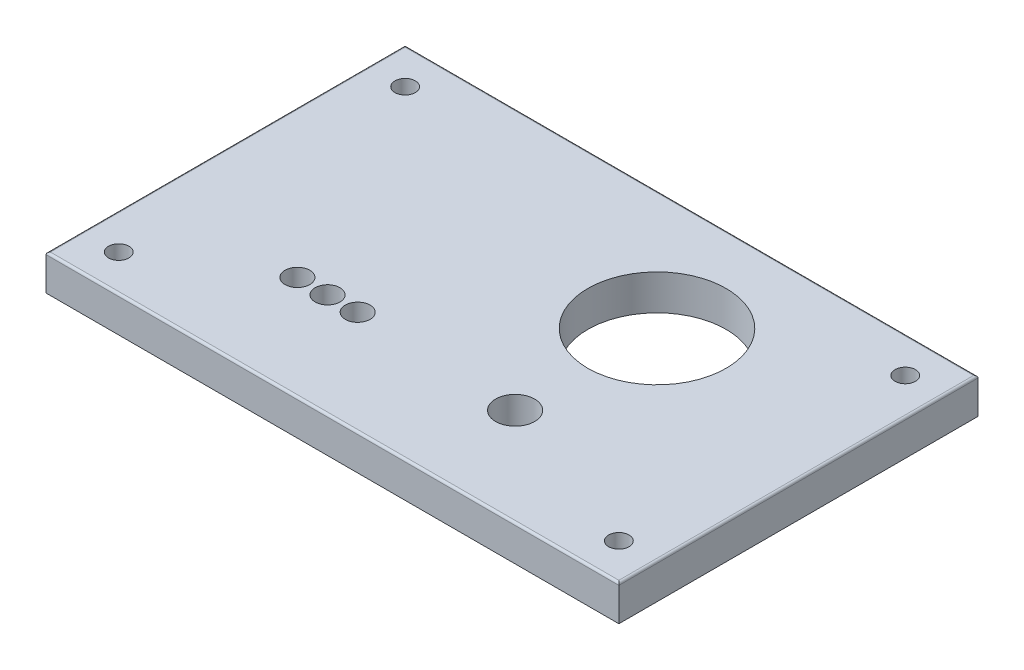
SolidWorks part; units mm, degrees
ref_plane "Front Plane" through (0, 0, 0) normal (0, 0, 1) x (1, 0, 0)
ref_plane "Top Plane" through (0, 0, 0) normal (0, 1, 0) x (1, 0, 0)
ref_plane "Right Plane" through (0, 0, 0) normal (1, 0, 0) x (0, 0, -1)
sketch "Sketch1" plane through (0, 0, 0) normal (0, 1, 0) x (1, 0, 0)
  line L0 (32.3, 20.25) -> (32.3, 17.75) construction
  line L1 (-32.3, -20.25) -> (32.3, -20.25)
  line L2 (-32.3, -20.25) -> (-32.3, 20.25)
  line L3 (-32.3, 20.25) -> (32.3, 20.25)
  line L4 (32.3, -20.25) -> (32.3, 20.25)
  line L5 (-32.3, -20.25) -> (32.3, 20.25) construction
  line L6 (-32.3, 20.25) -> (32.3, -20.25) construction
  line L7 (32.3, 17.75) -> (29.8, 17.75) construction
  line L8 (29.8, 17.75) -> (29.8, 20.25) construction
  line L9 (-2.2, 6.75) -> (1.8, 6.75) construction
  line L10 (29.8, 17.75) -> (-2.2, 17.75) construction
  line L11 (29.8, 17.75) -> (29.8, -4.25) construction
  line L12 (29.8, -4.25) -> (-2.2, -4.25) construction
  line L13 (-2.2, 17.75) -> (-2.2, -4.25)
  line L14 (1.8, 6.75) -> (9.6, 6.75) construction
  line L15 (9.6, 6.75) -> (9.6, -4.25) construction
  line L16 (9.6, -4.25) -> (9.6, -6.75) construction
  line L17 (9.6, -6.75) -> (9.6, -11.75) construction
  line L18 (-2.2, 6.75) -> (-4.7, 6.75) construction
  line L19 (-4.7, 6.75) -> (-19.8, 6.75) construction
  line L20 (-12.25, 6.75) -> (-12.25, 18.55) construction
  line L21 (-12.25, 18.55) -> (-4.7, 18.55)
  line L22 (-12.25, 18.55) -> (-19.8, 18.55) construction
  line L23 (-19.8, -8.55) -> (-4.7, -8.55) construction
  line L24 (-19.8, 18.55) -> (-4.7, 18.55) construction
  line L25 (-19.8, 18.55) -> (-19.8, -6.55) construction
  line L26 (-19.8, -6.55) -> (-4.7, -6.55) construction
  line L27 (-4.7, 18.55) -> (-4.7, -6.55) construction
  line L28 (-10.85, -8.55) -> (-10.25, -8.55) construction
  line L29 (-10.25, -8.55) -> (-8.85, -8.55) construction
  line L30 (-13.65, -8.55) -> (-14.25, -8.55) construction
  line L31 (-14.25, -8.55) -> (-15.65, -8.55) construction
  circle A0 centre (9.6, 6.75) radius 7.8
  circle A1 centre (9.6, -9.25) radius 2.2
  circle A2 centre (-12.25, -8.55) radius 1.4
  circle A3 centre (-8.85, -8.55) radius 1.4
  circle A4 centre (-15.65, -8.55) radius 1.4
  point P0 (0, 0)
  dimension "D9" = 15.6
  dimension "D11" = 5
  dimension "D12" = 4.4
  dimension "D20" = 2.8
  dimension "D23" = 2.8
  dimension "D26" = 2.8
  dimension "D1" = 40.5
  dimension "D2" = 64.6
  dimension "D3" = 2.5
  dimension "D4" = 2.5
  dimension "D5" = 32
  dimension "D6" = 22
  dimension "D7" = 4
  dimension "D8" = 7.8
  dimension "D10" = 2.5
  dimension "D13" = 2.5
  dimension "D14" = 15.1
  dimension "D15" = 7.55
  dimension "D16" = 7.55
  dimension "D17" = 25.1
  dimension "D18" = 15.1
  dimension "D21" = 0.6
  dimension "D22" = 1.4
  dimension "D24" = 0.6
  dimension "D25" = 1.4
  dimension "D19" = 2
extrude "Boss-Extrude3" add sketch "Sketch1" along normal blind 4
sketch "Sketch6" plane through (0, 4, 0) normal (0, 1, 0) x (1, 0, 0)
  line L0 (-24.1, 16.15) -> (-32.3, 16.15) construction
  line L1 (-32.3, 20.25) -> (-24.1, 20.25) construction
  line L2 (-32.3, 20.25) -> (-32.3, 12.05) construction
  line L3 (-32.3, 12.05) -> (-24.1, 12.05) construction
  line L4 (-24.1, 20.25) -> (-24.1, 12.05) construction
  line L5 (0, 20.25) -> (0, 27.4316) construction
  line L6 (-32.3, 20.25) -> (32.3, 20.25) construction
  line L7 (0, 0) -> (0, -20.8453) construction
  line L8 (0, 0) -> (32.3, 0) construction
  line L9 (32.3, -20.25) -> (32.3, 20.25) construction
  line L10 (32.3, 0) -> (50.1979, 0) construction
  circle A0 centre (-28.2, 16.15) radius 1.15
  circle A1 centre (28.2, 16.15) radius 1.15
  circle A2 centre (28.2, -16.15) radius 1.15
  circle A3 centre (-28.2, -16.15) radius 1.15
  dimension "D1" = 8.2
  dimension "D2" = 8.2
extrude "Cut-Extrude4" cut sketch "Sketch6" against normal blind 5
fillet "Fillet4" radius 0.25 4 edges at (32.3, 4, 0) (-32.3, 4, 0) (0, 4, 20.25) (0, 4, -20.25)
